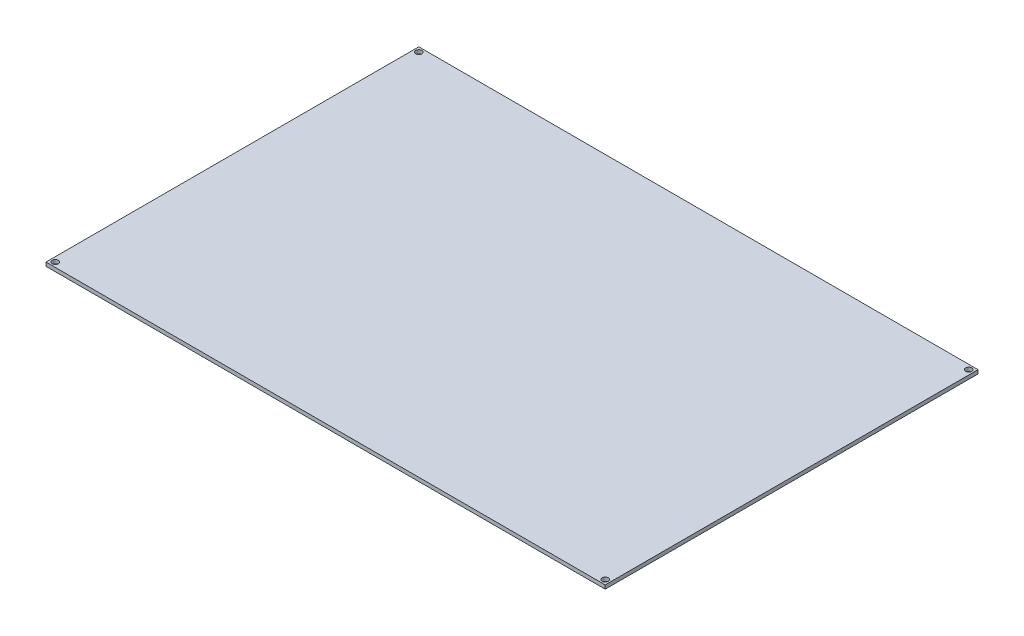
SolidWorks part; units mm, degrees
ref_plane "Front Plane" through (0, 0, 0) normal (0, 0, 1) x (1, 0, 0)
ref_plane "Top Plane" through (0, 0, 0) normal (0, 1, 0) x (1, 0, 0)
ref_plane "Right Plane" through (0, 0, 0) normal (1, 0, 0) x (0, 0, -1)
sketch "Sketch1" plane through (0, 0, 0) normal (0, 1, 0) x (1, 0, 0)
  line L0 (5, 0) -> (5, 5) construction
  line L1 (0, 0) -> (300, 0)
  line L2 (0, 0) -> (0, 200)
  line L3 (0, 200) -> (300, 200)
  line L4 (300, 0) -> (300, 200)
  line L5 (5, 5) -> (0, 5) construction
  line L6 (5, 2.5) -> (0, 2.5) construction
  line L7 (2.5, 5) -> (2.5, 0) construction
  line L8 (150, 200) -> (150, 0) construction
  line L9 (0, 100) -> (300, 100) construction
  circle A0 centre (2.5, 2.5) radius 1.65
  circle A1 centre (297.5, 2.5) radius 1.65
  circle A2 centre (297.5, 197.5) radius 1.65
  circle A3 centre (2.5, 197.5) radius 1.65
  dimension "D5" = 3.3
  dimension "D1" = 200
  dimension "D2" = 300
  dimension "D3" = 5
  dimension "D4" = 5
extrude "Boss-Extrude1" add sketch "Sketch1" along normal blind 2
